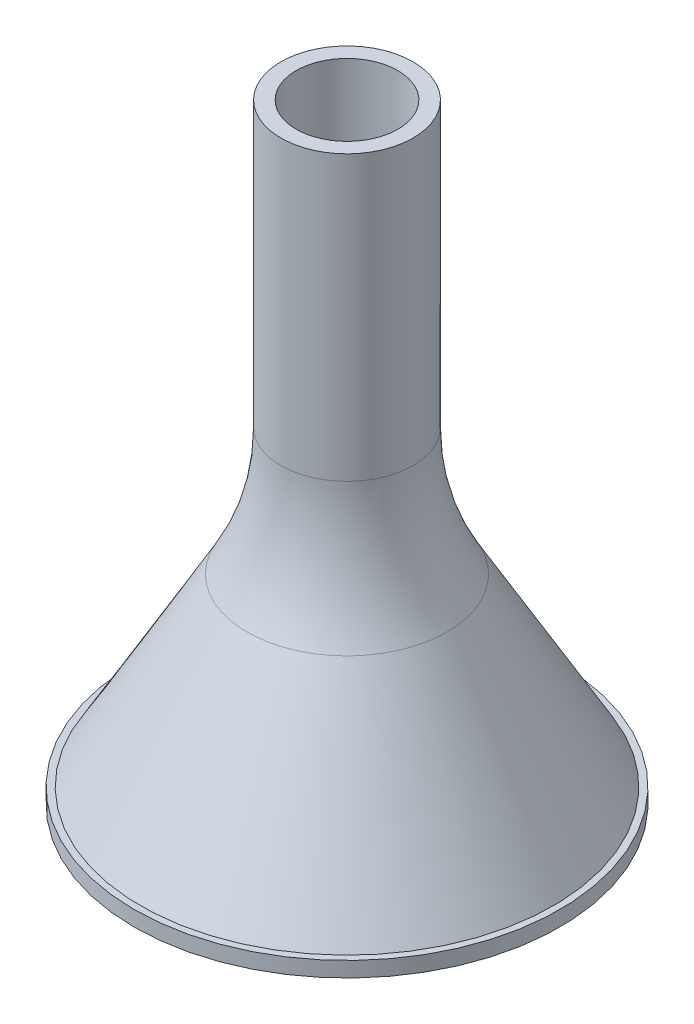
SolidWorks part; units mm, degrees
ref_plane "前视基准面" through (0, 0, 0) normal (0, 0, 1) x (1, 0, 0)
ref_plane "上视基准面" through (0, 0, 0) normal (0, 1, 0) x (1, 0, 0)
ref_plane "右视基准面" through (0, 0, 0) normal (1, 0, 0) x (0, 0, -1)
sketch "草图1" plane through (0, 0, 0) normal (0, 0, 1) x (1, 0, 0)
  line L0 (0, 0) -> (0, 87.4539) construction
  line L1 (10, 120) -> (10, 50)
  line L6 (10, 50) -> (38.8675, 0)
  line L7 (0, 0) -> (35.3553, 0) construction
  line L8 (38.8675, 0) -> (41.8675, 0)
  dimension "D1" = 60
  dimension "D2" = 50
  dimension "D3" = 20
  dimension "D4" = 70
  dimension "D5" = 3
revolve "旋转-薄壁1" add sketch "草图1" angle 360 about L0 wall 3
ref_plane "基准面1" through (0, 50, 0) normal (0, 1, 0) x (1, 0, 0)
sketch "草图2" plane through (0, 50, 0) normal (0, 1, 0) x (1, 0, 0)
  circle A0 centre (0, 0) radius 10 construction
  circle A1 centre (0, 0) radius 10
  circle A2 centre (0, 0) radius 4
  dimension "D1" = 8
extrude "凸台-拉伸1" add sketch "草图2" along normal blind 5
fillet "圆角1" radius 50 1 edges at (0, 50.8038, -13)
